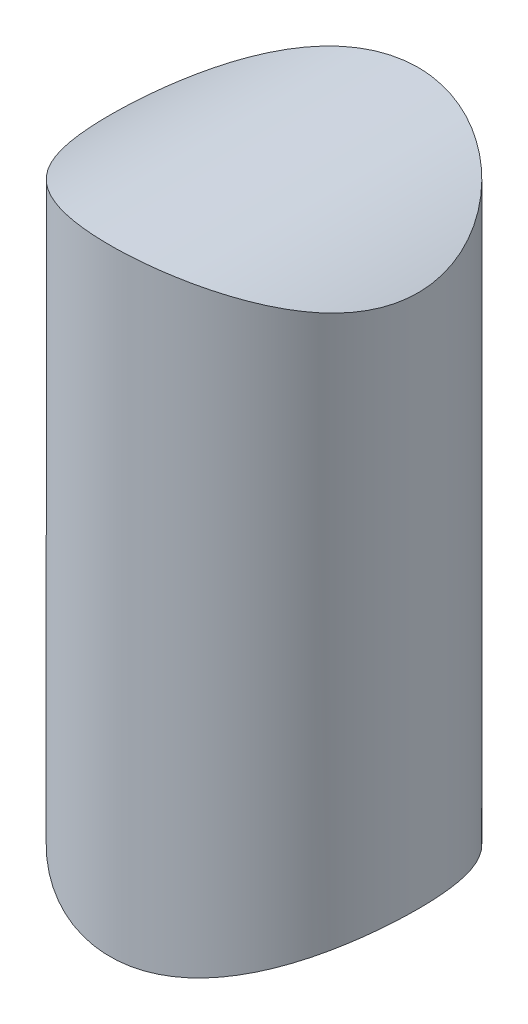
SolidWorks part; units mm, degrees
ref_plane "Front Plane" through (0, 0, 0) normal (0, 0, 1) x (1, 0, 0)
ref_plane "Top Plane" through (0, 0, 0) normal (0, 1, 0) x (1, 0, 0)
ref_plane "Right Plane" through (0, 0, 0) normal (1, 0, 0) x (0, 0, -1)
sketch "Sketch1" plane through (0, 0, 0) normal (0, 1, 0) x (1, 0, 0)
  circle A0 centre (0, 0) radius 2
  dimension "D1" = 4
extrude "Boss-Extrude1" add sketch "Sketch1" along normal blind 20
sketch "Sketch2" plane through (0, 0, 0) normal (0, 0, 1) x (1, 0, 0)
  circle A0 centre (0, 10.9128) radius 4
  point P2 (0, 0)
  dimension "D1" = 8
extrude "Cut-Extrude2" cut sketch "Sketch2" against normal mid plane 20 flip side to cut contours A0
